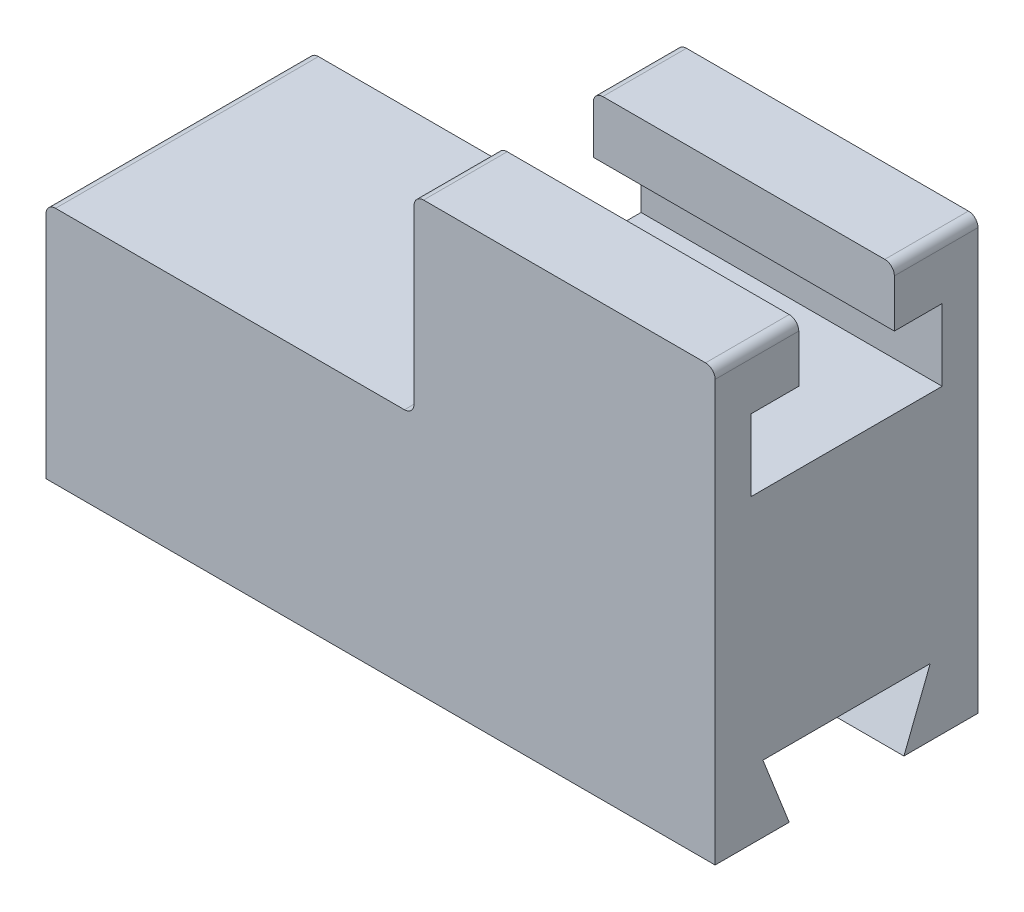
SolidWorks part; units mm, degrees
ref_plane "Front Plane" through (0, 0, 0) normal (0, 0, 1) x (1, 0, 0)
ref_plane "Top Plane" through (0, 0, 0) normal (0, 1, 0) x (1, 0, 0)
ref_plane "Right Plane" through (0, 0, 0) normal (1, 0, 0) x (0, 0, -1)
sketch "Sketch1" plane through (0, 0, 0) normal (0, 0, 1) x (1, 0, 0)
  line L0 (-70, 0) -> (70, 0)
  line L1 (70, 0) -> (70, 90)
  line L2 (70, 90) -> (7, 90)
  line L3 (7, 90) -> (7, 50)
  line L4 (7, 50) -> (-70, 50)
  line L5 (-70, 50) -> (-70, 0)
  point P3 (8.3058, 98.2005)
  point P4 (89.6497, 90)
  point P5 (-6.0675, 90)
  point P6 (7, 42.5414)
  point P7 (-93.9028, 50)
  point P9 (-70, 62.384)
  point P11 (7, 90)
  point P14 (7, 50)
  point P15 (13.7067, 50)
  point P17 (70, 96.9415)
  dimension "D5" = 63
  dimension "D1" = 70
  dimension "D2" = 140
  dimension "D3" = 90
  dimension "D4" = 40
extrude "Boss-Extrude1" add sketch "Sketch1" along normal mid plane 55
sketch "Sketch3" plane through (-70, 0, 0) normal (-1, 0, 0) x (0, 0, 1)
  line L0 (-12, 0) -> (-17.5, 14)
  line L1 (27.5, 0) -> (-27.5, 0) construction
  line L2 (-17.5, 14) -> (17.5, 14)
  line L3 (17.5, 14) -> (12, 0)
  line L4 (0, 25.796) -> (0, -19.9829) construction
  line L5 (-12, 0) -> (12, 0)
  dimension "D1" = 12
  dimension "D2" = 24
  dimension "D3" = 35
  dimension "D4" = 17.5
  dimension "D5" = 14
extrude "Cut-Extrude1" cut sketch "Sketch3" against normal through all
sketch "Sketch5" plane through (70, 0, 0) normal (1, 0, 0) x (0, 0, -1)
  line L0 (0, -4.1539) -> (0, 114.9694) construction
  line L1 (-10, 90) -> (-10, 78)
  line L2 (-27.5, 90) -> (27.5, 90) construction
  line L3 (-10, 78) -> (-20, 78)
  line L4 (-20, 78) -> (-20, 63)
  line L5 (-20, 63) -> (20, 63)
  line L6 (20, 63) -> (20, 78)
  line L7 (20, 78) -> (10, 78)
  line L8 (10, 78) -> (10, 90)
  line L9 (10, 90) -> (-10, 90)
  dimension "D1" = 40
  dimension "D2" = 20
  dimension "D3" = 12
  dimension "D4" = 12
  dimension "D5" = 27
  dimension "D6" = 20
  dimension "D7" = 10
extrude "Cut-Extrude2" cut sketch "Sketch5" against normal blind 63
sketch "Sketch6" plane through (0, 0, 0) normal (0, 0, 1) x (1, 0, 0)
  line L0 (-30, 14) -> (-30, 20)
  line L1 (-20, 30) -> (28.5, 30)
  line L2 (38.5, 40) -> (38.5, 63)
  line L3 (70, 14) -> (-70, 14) construction
  line L4 (7, 63) -> (70, 63) construction
  line L5 (70, 0) -> (70, 90) construction
  line L7 (-70, 0) -> (70, 0) construction
  arc A0 (38.5, 40) -> (28.5, 30) centre (28.5, 40) cw
  arc A1 (-20, 30) -> (-30, 20) centre (-20, 20) ccw
  dimension "D1" = 10
  dimension "D2" = 100
  dimension "D3" = 30
ref_plane "Plane1" through (38.5, 63, 0) normal (0, 1, 0) x (1, 0, 0)
sketch "Sketch7" plane through (38.5, 63, 0) normal (0, 1, 0) x (1, 0, 0)
  circle A0 centre (0.2196, 0) radius 8
  dimension "D1" = 16
sweep "Cut-Sweep2" cut profiles "Sketch7" path "Sketch6"
fillet "Fillet1" radius 2 4 edges at (-70, 50, 0) (7, 50, 0) (7, 90, -18.75) (7, 90, 18.75)
fillet "Fillet2" radius 2 2 edges at (70, 90, -18.75) (70, 90, 18.75)
